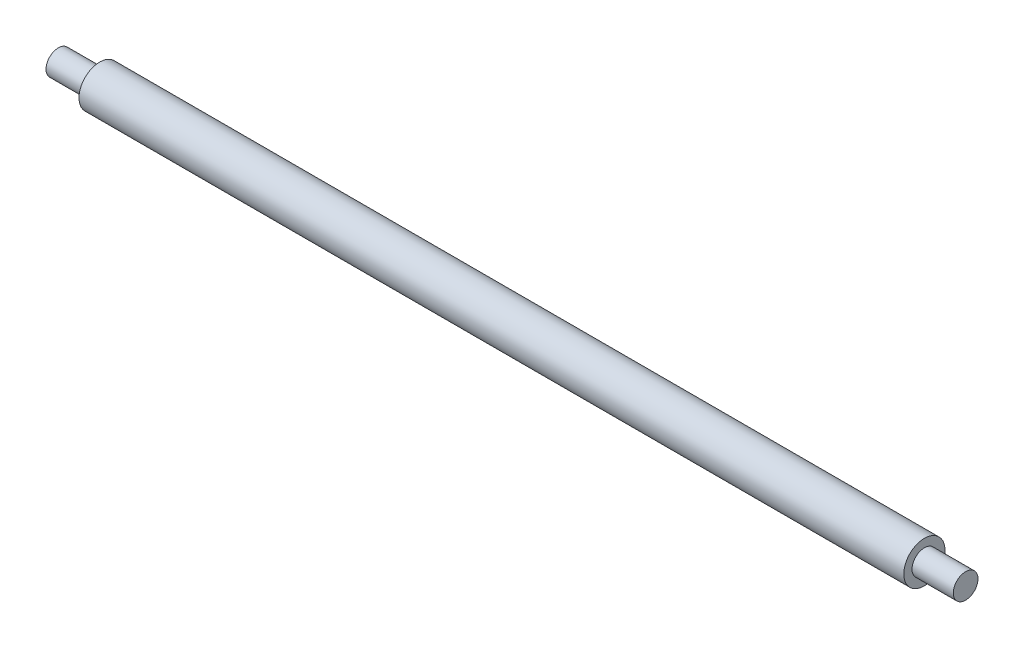
SolidWorks part; units mm, degrees
material "Acero al carbono fundido"
ref_plane "Alzado" through (0, 0, 0) normal (0, 0, 1) x (1, 0, 0)
ref_plane "Planta" through (0, 0, 0) normal (0, 1, 0) x (1, 0, 0)
ref_plane "Vista lateral" through (0, 0, 0) normal (1, 0, 0) x (0, 0, -1)
sketch "Croquis1" plane through (0, 0, 0) normal (1, 0, 0) x (0, 0, -1)
  circle A0 centre (0, 0) radius 5
  dimension "D1" = 10
extrude "Saliente-Extruir1" add sketch "Croquis1" along normal blind 220
sketch "Croquis2" plane through (0, 0, 0) normal (-1, 0, 0) x (0, 0, 1)
  circle A0 centre (0, 0) radius 5
extrude "Saliente-Extruir2" add sketch "Croquis2" against normal blind 10
sketch "Croquis3" plane through (220, 0, 0) normal (1, 0, 0) x (0, 0, -1)
  circle A0 centre (0, 0) radius 5
extrude "Saliente-Extruir3" add sketch "Croquis3" against normal blind 10
sketch "Croquis4" plane through (0, 0, 0) normal (-1, 0, 0) x (0, 0, 1)
  circle A0 centre (0, 0) radius 3
extrude "Cortar-Extruir1" cut sketch "Croquis4" against normal blind 10 flip side to cut
sketch "Croquis5" plane through (220, 0, 0) normal (1, 0, 0) x (0, 0, -1)
  circle A0 centre (0, 0) radius 3
extrude "Cortar-Extruir2" cut sketch "Croquis5" against normal blind 10 flip side to cut
